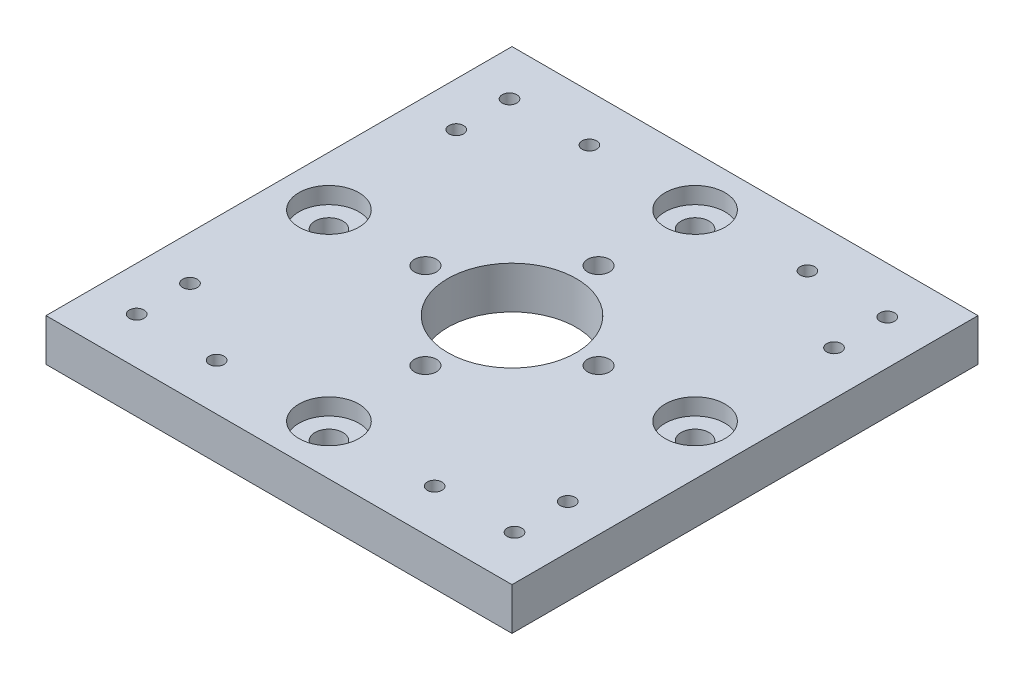
SolidWorks part; units mm, degrees
ref_plane "Front Plane" through (0, 0, 0) normal (0, 0, 1) x (1, 0, 0)
ref_plane "Top Plane" through (0, 0, 0) normal (0, 1, 0) x (1, 0, 0)
ref_plane "Right Plane" through (0, 0, 0) normal (1, 0, 0) x (0, 0, -1)
sketch "Sketch1" plane through (0, 0, 0) normal (0, 1, 0) x (1, 0, 0)
  line L1 (-35, -35) -> (35, -35)
  line L2 (-35, -35) -> (-35, 35)
  line L3 (-35, 35) -> (35, 35)
  line L4 (35, -35) -> (35, 35)
  line L5 (-35, -35) -> (35, 35) construction
  line L6 (-35, 35) -> (35, -35) construction
  circle A1 centre (0, 0) radius 13
  circle A2 centre (0, 13) radius 1.65
  circle A3 centre (13, 0) radius 1.65
  circle A4 centre (0, -13) radius 1.65
  circle A5 centre (-13, 0) radius 1.65
  point P1 (0, 0)
  dimension "D1" = 26
  dimension "D2" = 3.3
  dimension "D3" = 70
  dimension "D4" = 70
extrude "Boss-Extrude1" add sketch "Sketch1" along normal blind 6.35
sketch "Sketch2" plane through (0, 6.35, 0) normal (0, 1, 0) x (1, 0, 0)
  line L0 (0, 0) -> (0, 50000) construction
  line L1 (0, 0) -> (-50000, 0) construction
  circle A0 centre (16.375, 28) radius 1.1
  circle A1 centre (28.375, 28) radius 1.1
  circle A2 centre (28.375, 20) radius 1.1
  circle A3 centre (-28.375, 20) radius 1.1
  circle A4 centre (-28.375, 28) radius 1.1
  circle A5 centre (-16.375, 28) radius 1.1
  circle A6 centre (28.375, -20) radius 1.1
  circle A7 centre (28.375, -28) radius 1.1
  circle A8 centre (16.375, -28) radius 1.1
  circle A9 centre (-16.375, -28) radius 1.1
  circle A10 centre (-28.375, -20) radius 1.1
  circle A11 centre (-28.375, -28) radius 1.1
  dimension "D1" = 2.2
  dimension "D2" = 8
  dimension "D3" = 12
  dimension "D5" = 16.375
  dimension "D4" = 20
extrude "Cut-Extrude1" cut sketch "Sketch2" against normal up to next
sketch "Sketch3" plane through (0, 6.35, 0) normal (0, 1, 0) x (1, 0, 0)
  circle A0 centre (0, 0) radius 9.65
  dimension "D1" = 19.3
extrude "Cut-Extrude2" cut sketch "Sketch3" against normal up to next
sketch "Sketch4" plane through (0, 6.35, 0) normal (0, 1, 0) x (1, 0, 0)
  circle A0 centre (0, 0) radius 27.5
  circle A1 centre (0, 27.5) radius 2.1
  circle A2 centre (27.5, 0) radius 2.1
  circle A3 centre (0, -27.5) radius 2.1
  circle A4 centre (-27.5, 0) radius 2.1
  point P13 (0, 0)
  dimension "D1" = 55
  dimension "D2" = 4.2
  dimension "D3" = 4
extrude "Cut-Extrude3" cut sketch "Sketch4" against normal up to next contours A0 A4 | A0 A4 | A0 A1 | A0 A1 | A0 A2 | A0 A2 | A0 A3 | A0 A3
sketch "Sketch5" plane through (0, 6.35, 0) normal (0, 1, 0) x (1, 0, 0)
  circle A0 centre (0, 27.5) radius 4.5
  circle A1 centre (27.5, 0) radius 4.5
  circle A2 centre (0, -27.5) radius 4.5
  circle A3 centre (-27.5, 0) radius 4.5
  dimension "D1" = 9
extrude "Cut-Extrude4" cut sketch "Sketch5" against normal blind 2.5
